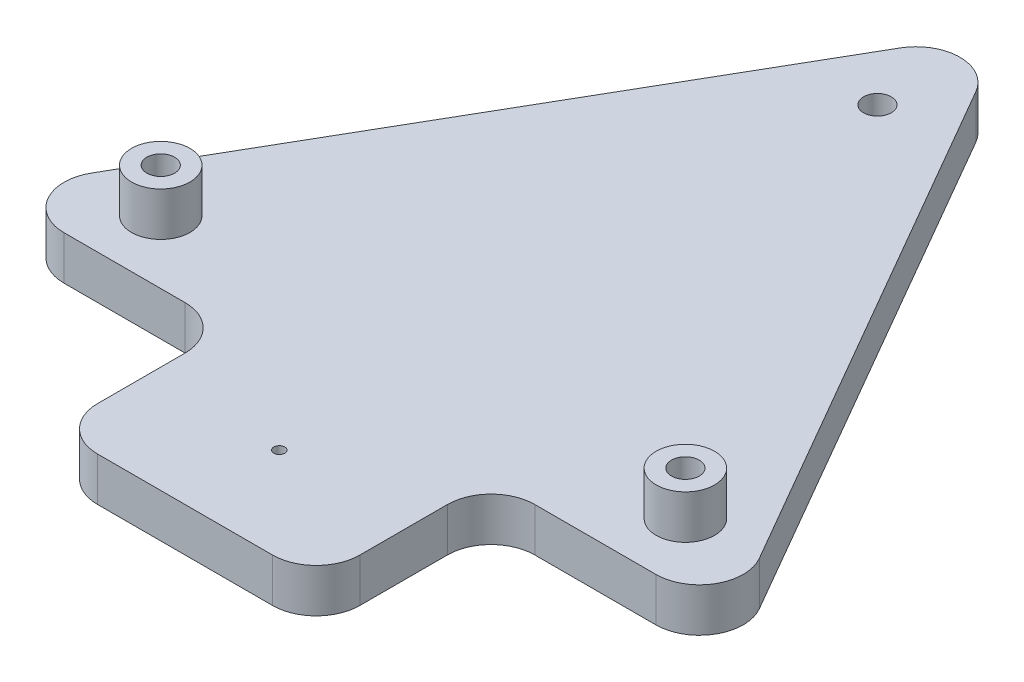
SolidWorks part; units mm, degrees
ref_plane "Front Plane" through (0, 0, 0) normal (0, 0, 1) x (1, 0, 0)
ref_plane "Top Plane" through (0, 0, 0) normal (0, 1, 0) x (1, 0, 0)
ref_plane "Right Plane" through (0, 0, 0) normal (1, 0, 0) x (0, 0, -1)
sketch "Sketch1" plane through (0, 0, 0) normal (0, 1, 0) x (1, 0, 0)
  line L0 (-67.6795, 0) -> (-40, 0)
  line L1 (-76.3397, 15) -> (-8.6603, 132.2243)
  line L2 (8.6603, 132.2243) -> (76.3397, 15)
  line L3 (-85, 0) -> (42.5, 73.6122) construction
  line L4 (85, 0) -> (-42.5, 73.6122) construction
  line L5 (0, 0) -> (0, 147.2243) construction
  line L6 (0, 118.3568) -> (-60, 14.4338) construction
  line L7 (-60, 14.4338) -> (60, 14.4338) construction
  line L8 (60, 14.4338) -> (0, 118.3568) construction
  line L9 (-30, -10) -> (-30, -30)
  line L10 (-20, -40) -> (20, -40)
  line L11 (30, -30) -> (30, -10)
  line L12 (40, 0) -> (67.6795, 0)
  circle A0 centre (-60, 14.4338) radius 3.175
  circle A1 centre (0, 118.3568) radius 3.175
  circle A2 centre (60, 14.4338) radius 3.175
  arc A3 (-30, -10) -> (-40, 0) centre (-40, -10) ccw
  arc A4 (30, -10) -> (40, 0) centre (40, -10) cw
  arc A5 (20, -40) -> (30, -30) centre (20, -30) ccw
  arc A6 (-30, -30) -> (-20, -40) centre (-20, -30) ccw
  arc A7 (67.6795, 0) -> (76.3397, 15) centre (67.6795, 10) ccw
  arc A8 (-67.6795, 0) -> (-76.3397, 15) centre (-67.6795, 10) cw
  arc A9 (-8.6603, 132.2243) -> (8.6603, 132.2243) centre (0, 127.2243) cw
  circle A10 centre (0, -18.4502) radius 1.25
  point P4 (0, 0)
  point P22 (-30, 0)
  point P25 (30, 0)
  point P30 (-30, -40)
  point P40 (0, -18.4502)
  dimension "D1" = 30
  dimension "D4" = 10
  dimension "D6" = 6.35
  dimension "D7" = 6.35
  dimension "D8" = 6.35
  dimension "D2" = 30
  dimension "D3" = 40
  dimension "D5" = 136.807
extrude "Boss-Extrude2" add sketch "Sketch1" along normal blind 10
sketch "Sketch2" plane through (0, 10, 0) normal (0, 1, 0) x (1, 0, 0)
  circle A0 centre (60, 14.4338) radius 3.175 construction
  circle A2 centre (-60, 14.4338) radius 3.175 construction
  circle A3 centre (60, 14.4338) radius 3.175
  circle A5 centre (-60, 14.4338) radius 3.175
  circle A6 centre (-60, 14.4338) radius 6.675
  circle A8 centre (60, 14.4338) radius 6.675
  dimension "D1" = 3.5
extrude "Boss-Extrude3" add sketch "Sketch2" along normal blind 10
